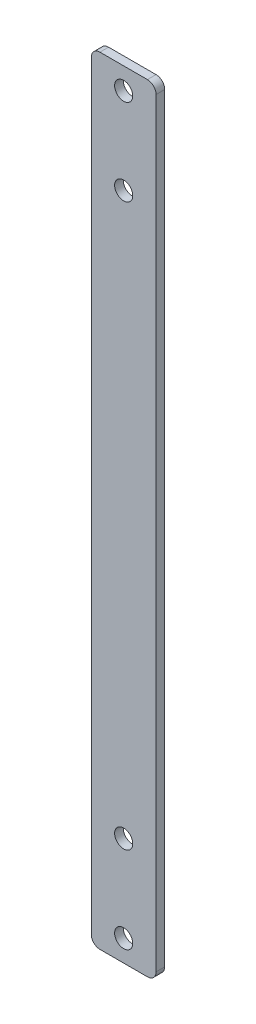
SolidWorks part; units mm, degrees
ref_plane "Спереди" through (0, 0, 0) normal (0, 0, 1) x (1, 0, 0)
ref_plane "Сверху" through (0, 0, 0) normal (0, 1, 0) x (1, 0, 0)
ref_plane "Справа" through (0, 0, 0) normal (1, 0, 0) x (0, 0, -1)
sketch "Эскиз1" plane through (0, 0, 0) normal (0, 0, 1) x (1, 0, 0)
  line L0 (0, 67.7129) -> (0, -93374.896) construction
  line L1 (-7.5, 173) -> (-7.5, -3)
  line L2 (7.5, 173) -> (7.5, -3)
  line L3 (-5.5, 175) -> (5.5, 175)
  line L4 (-5.5, -5) -> (5.5, -5)
  line L5 (12.2202, 85) -> (-12.0806, 85) construction
  circle A0 centre (0, 170) radius 2.1
  circle A1 centre (0, 150) radius 2.1
  circle A2 centre (0, 20) radius 2.1
  circle A3 centre (0, 0) radius 2.1
  arc A4 (5.5, -5) -> (7.5, -3) centre (5.5, -3) ccw
  arc A5 (-7.5, -3) -> (-5.5, -5) centre (-5.5, -3) ccw
  arc A6 (5.5, 175) -> (7.5, 173) centre (5.5, 173) cw
  arc A7 (-5.5, 175) -> (-7.5, 173) centre (-5.5, 173) ccw
  point P21 (7.5, -5)
  point P24 (-7.5, -5)
  point P27 (7.5, 175)
  point P30 (-7.5, 175)
  dimension "D3" = 4.2
  dimension "D4" = 4.2
  dimension "D7" = 2
  dimension "D1" = 180
  dimension "D2" = 15
  dimension "D5" = 20
  dimension "D6" = 5
extrude "Бобышка-Вытянуть1" add sketch "Эскиз1" along normal blind 2 contours A0 | A1 | A3 | A2 | L1 A5 L4 A4 L2 A6 L3 A7
